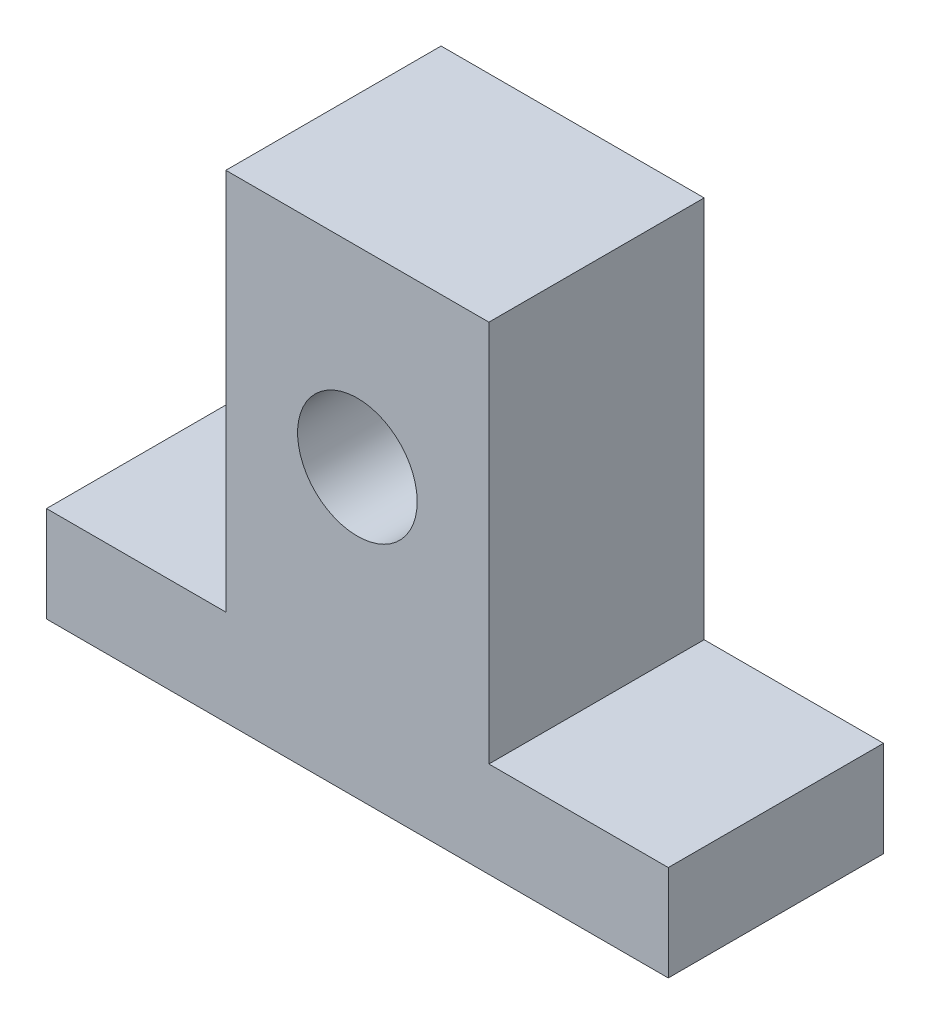
SolidWorks part; units mm, degrees
ref_plane "Front Plane" through (0, 0, 0) normal (0, 0, 1) x (1, 0, 0)
ref_plane "Top Plane" through (0, 0, 0) normal (0, 1, 0) x (1, 0, 0)
ref_plane "Right Plane" through (0, 0, 0) normal (1, 0, 0) x (0, 0, -1)
sketch "Sketch1" plane through (0, 0, 0) normal (0, 0, 1) x (1, 0, 0)
  line L0 (0, 28.575) -> (0, 3.175) construction
  line L1 (-20.6375, -3.175) -> (20.6375, -3.175)
  line L2 (-20.6375, -3.175) -> (-20.6375, 3.175)
  line L3 (-20.6375, 3.175) -> (20.6375, 3.175)
  line L4 (20.6375, -3.175) -> (20.6375, 3.175)
  line L5 (-20.6375, -3.175) -> (20.6375, 3.175) construction
  line L6 (-20.6375, 3.175) -> (20.6375, -3.175) construction
  line L7 (-8.7312, 3.175) -> (8.7312, 3.175)
  line L8 (-8.7312, 3.175) -> (-8.7312, 28.575)
  line L9 (-8.7312, 28.575) -> (8.7312, 28.575)
  line L10 (8.7312, 3.175) -> (8.7312, 28.575)
  circle A0 centre (0, 15.875) radius 3.9688
  point P0 (0, 0)
  dimension "D5" = 7.9375
  dimension "D1" = 41.275
  dimension "D2" = 6.35
  dimension "D3" = 17.4625
  dimension "D4" = 25.4
  dimension "D6" = 12.7
extrude "Boss-Extrude1" add sketch "Sketch1" along normal blind 14.2875 contours L3 L10 L9 L8 | L1 L4 L3 L2
